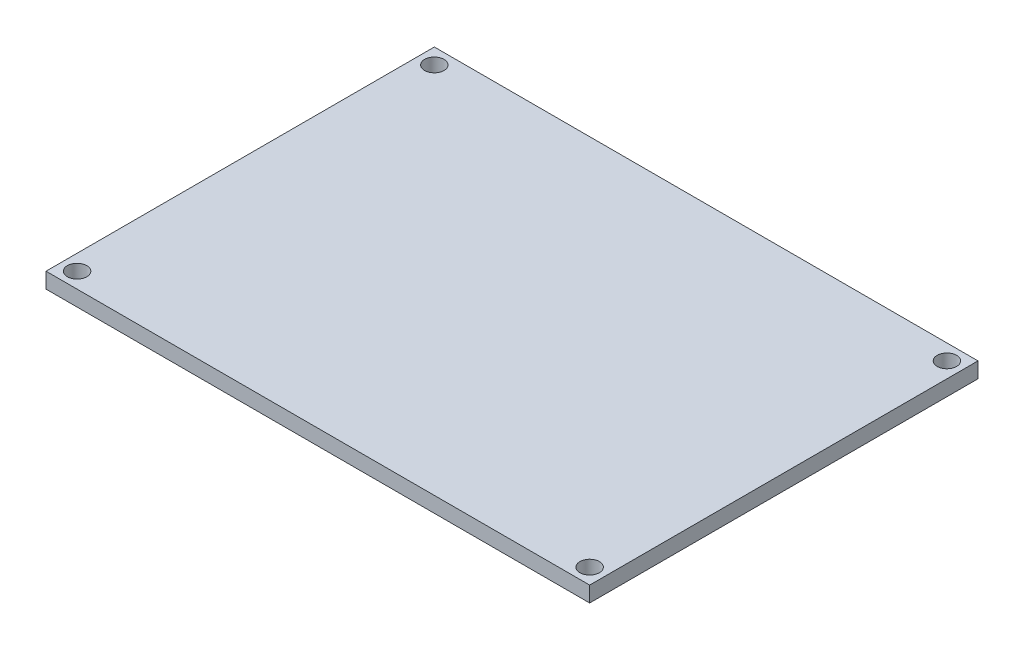
SolidWorks part; units mm, degrees
ref_plane "Front Plane" through (0, 0, 0) normal (0, 0, 1) x (1, 0, 0)
ref_plane "Top Plane" through (0, 0, 0) normal (0, 1, 0) x (1, 0, 0)
ref_plane "Right Plane" through (0, 0, 0) normal (1, 0, 0) x (0, 0, -1)
sketch "Sketch1" plane through (0, 0, 0) normal (0, 1, 0) x (1, 0, 0)
  line L1 (-35, 25) -> (35, 25)
  line L2 (-35, 25) -> (-35, -25)
  line L3 (-35, -25) -> (35, -25)
  line L4 (35, 25) -> (35, -25)
  line L5 (-35, 25) -> (35, -25) construction
  line L6 (-35, -25) -> (35, 25) construction
  point P0 (0, 0)
  dimension "D1" = 70
  dimension "D2" = 50
extrude "Boss-Extrude1" add sketch "Sketch1" along normal blind 2
sketch "Sketch2" plane through (0, 0, 0) normal (0, -1, 0) x (1, 0, 0)
  line L1 (33, -23) -> (-33, -23) construction
  line L2 (33, -23) -> (33, 23) construction
  line L3 (33, 23) -> (-33, 23) construction
  line L4 (-33, -23) -> (-33, 23) construction
  line L5 (33, -23) -> (-33, 23) construction
  line L6 (33, 23) -> (-33, -23) construction
  circle A0 centre (-33, 23) radius 1.25
  circle A1 centre (33, 23) radius 1.25
  circle A2 centre (33, -23) radius 1.25
  circle A3 centre (-33, -23) radius 1.25
  point P0 (0, 0)
  dimension "D3" = 2.5
  dimension "D1" = 66
  dimension "D2" = 46
extrude "Cut-Extrude1" cut sketch "Sketch2" against normal through all both and the other way through all
sketch "Sketch3" plane through (0, 0, 0) normal (0, -1, 0) x (1, 0, 0)
  line L0 (-35, 25) -> (35, -25) construction
  line L1 (-35, 25) -> (35, 25) construction
  line L2 (29.4, -21) -> (-29.4, -21)
  line L3 (29.4, -21) -> (29.4, 21)
  line L4 (29.4, 21) -> (-29.4, 21)
  line L5 (-29.4, -21) -> (-29.4, 21)
  line L6 (29.4, -21) -> (-29.4, 21) construction
  line L7 (29.4, 21) -> (-29.4, -21) construction
  point P2 (0, 0)
  dimension "D1" = 4
extrude "Cut-Extrude2" [suppressed] cut sketch "Sketch3" against normal through all both and the other way through all
